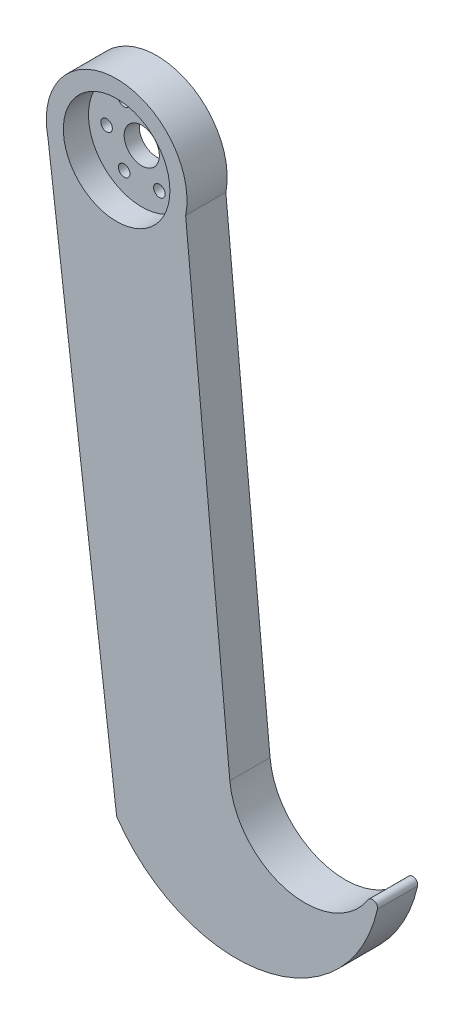
SolidWorks part; units mm, degrees
ref_plane "정면" through (0, 0, 0) normal (0, 0, 1) x (1, 0, 0)
ref_plane "윗면" through (0, 0, 0) normal (0, 1, 0) x (1, 0, 0)
ref_plane "우측면" through (0, 0, 0) normal (1, 0, 0) x (0, 0, -1)
sketch "스케치1" plane through (0, 0, 0) normal (0, 0, 1) x (1, 0, 0)
  circle A0 centre (0, 0) radius 14
  dimension "D1" = 28
extrude "보스-돌출1" add sketch "스케치1" along normal blind 8
sketch "스케치2" plane through (0, 0, 0) normal (0, 0, -1) x (-1, 0, 0)
  circle A0 centre (0, 0) radius 10.6
  dimension "D1" = 21.2
sketch "스케치3" plane through (0, 0, 8) normal (0, 0, 1) x (1, 0, 0)
  circle A0 centre (0, 0) radius 3.5
  dimension "D1" = 7
extrude "컷-돌출2" cut sketch "스케치3" against normal blind 10
sketch "스케치6" plane through (0, 0, 8) normal (0, 0, 1) x (1, 0, 0)
  line L0 (0, 0) -> (0, 18.4707) construction
  line L1 (-14, 37.9731) -> (-14, -35.8302) construction
  line L2 (14, 37.9731) -> (14, -35.8302) construction
  line L3 (13.7356, -2.7081) -> (22.5285, -95.7081)
  line L4 (-13.649, -3.1153) -> (0, -113.1153)
  arc A0 (22.5285, -95.7081) -> (52.4619, -94.2881) centre (37.4619, -94.2962) ccw
  circle A1 centre (0, 0) radius 14 construction
  arc A2 (0, -113.1153) -> (52.4619, -94.2881) centre (23.7903, -96.9007) ccw
  arc A3 (-13.649, -3.1153) -> (13.7356, -2.7081) centre (0, 0) ccw
  dimension "D3" = 15
  dimension "D1" = 93
  dimension "D2" = 110
extrude "보스-돌출3" add sketch "스케치6" against normal blind 8
fillet "필렛1" radius 1 1 edges at (52.4619, -94.2881, 4)
fillet "필렛2" radius 1 1 edges at (0, -113.1153, 4)
sketch "스케치8" plane through (0, 0, 8) normal (0, 0, 1) x (1, 0, 0)
  circle A0 centre (0, 0) radius 10.6
extrude "컷-돌출5" cut sketch "스케치8" against normal blind 5
sketch "스케치9" plane through (0, 0, 3) normal (0, 0, 1) x (1, 0, 0)
  circle A0 centre (7, 0) radius 1.15
  circle A1 centre (3.5, -6.0622) radius 1.15
  circle A2 centre (-3.5, -6.0622) radius 1.15
  circle A3 centre (-7, 0) radius 1.15
  circle A4 centre (-3.5, 6.0622) radius 1.15
  circle A5 centre (3.5, 6.0622) radius 1.15
  point P16 (0, 0)
  dimension "D1" = 2.3
  dimension "D2" = 7
  dimension "D3" = 6
extrude "컷-돌출6" cut sketch "스케치9" against normal blind 5
